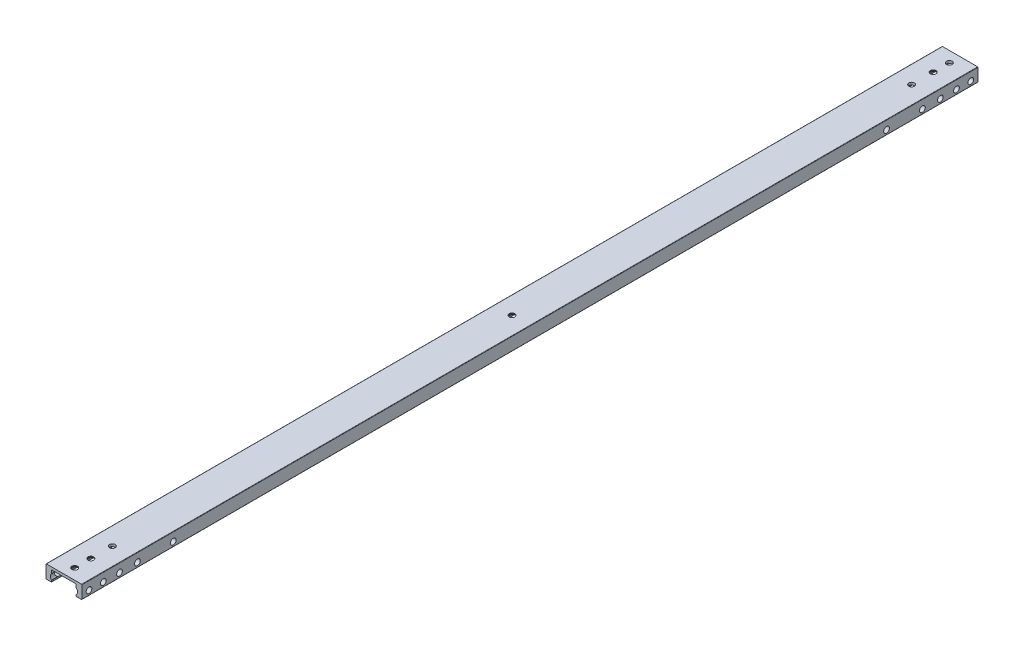
SolidWorks part; units mm, degrees
ref_plane "Front Plane" through (0, 0, 0) normal (0, 0, 1) x (1, 0, 0)
ref_plane "Top Plane" through (0, 0, 0) normal (0, 1, 0) x (1, 0, 0)
ref_plane "Right Plane" through (0, 0, 0) normal (1, 0, 0) x (0, 0, -1)
sketch "Sketch1" plane through (0, 0, 0) normal (0, 0, 1) x (1, 0, 0)
  line L0 (0, 3.7) -> (0, -3.7) construction
  line L1 (-10, -3.7) -> (10, -3.7)
  line L2 (-10, -3.7) -> (-10, 3.7)
  line L3 (-10, 3.7) -> (10, 3.7)
  line L4 (10, -3.7) -> (10, 3.7)
  line L5 (-10, -3.7) -> (10, 3.7) construction
  line L6 (-10, 3.7) -> (10, -3.7) construction
  line L7 (-6.85, -3.7) -> (6.85, -3.7)
  line L8 (-6.85, -3.7) -> (-6.85, 2.3)
  line L9 (-6.85, 2.3) -> (6.85, 2.3)
  line L10 (6.85, -3.7) -> (6.85, 2.3)
  line L11 (0, 2.3) -> (0, -3.7) construction
  point P0 (0, 0)
  dimension "D1" = 20
  dimension "D2" = 7.4
  dimension "D3" = 0
  dimension "D4" = 3.15
  dimension "D5" = 1.4
extrude "Boss-Extrude1" add sketch "Sketch1" along normal blind 500 contours L10 L1 L4 L3 L2 L8 L9
sketch "Sketch4" plane through (0, 2.3, 0) normal (0, -1, 0) x (1, 0, 0)
  line L0 (-10, 250) -> (10, 250) construction
  line L1 (-10, 500) -> (-10, 0) construction
  line L2 (10, 500) -> (10, 0) construction
  line L4 (-6.85, 500) -> (6.85, 500) construction
  circle A0 centre (0, 250) radius 1.6
  circle A1 centre (0, 15) radius 1.6
  circle A2 centre (0, 485) radius 1.6
  circle A5 centre (0, 494) radius 1.6
  circle A6 centre (0, 473) radius 1.6
  circle A7 centre (0, 27) radius 1.6
  circle A8 centre (0, 6) radius 1.6
  dimension "D1" = 3.2
  dimension "D2" = 3.2
  dimension "D4" = 3.2
  dimension "D6" = 9
  dimension "D7" = 3.2
  dimension "D3" = 235
  dimension "D5" = 15
  dimension "D8" = 12
extrude "Cut-Extrude1" cut sketch "Sketch4" against normal through all
sketch "Sketch5" plane through (0, 0, 500) normal (0, 0, 1) x (1, 0, 0)
  line L0 (0, 3.7) -> (0, -3.7178) construction
  line L1 (-10, 3.7) -> (10, 3.7) construction
  line L2 (-10, -3.7) -> (-6.85, -3.7) construction
  circle A0 centre (-5.7299, -1.15) radius 1.9
  circle A1 centre (5.7299, -1.15) radius 1.9
  dimension "D1" = 3.8
  dimension "D2" = 2.55
extrude "Cut-Extrude2" cut sketch "Sketch5" against normal through all
fillet "Fillet1" radius 0.2 12 edges at (-10, 3.7, 250) (-10, -3.7, 250) (-6.85, -3.7, 250) (-6.85, 0.3848, 250) (-6.85, -2.6848, 250) (-6.85, 2.3, 250) (10, 3.7, 250) (6.85, 2.3, 250) (6.85, -2.6848, 250) (6.85, 0.3848, 250) (6.85, -3.7, 250) (10, -3.7, 250)
sketch "Sketch6" plane through (-6.85, 0, 0) normal (1, 0, 0) x (0, 0, -1)
  line L0 (0, -2.6277) -> (0, 0.3277) construction
  line L1 (0, -2.6277) -> (0, 0.3277)
  line L2 (-250, 3.7) -> (-250, -3.5) construction
  line L3 (-500, 3.7) -> (0, 3.7) construction
  line L4 (-500, -3.5) -> (0, -3.5) construction
  circle A0 centre (-4, -1.15) radius 1.6
  circle A1 centre (-496, -1.15) radius 1.6
  circle A7 centre (-488, -1.15) radius 1.6
  circle A10 centre (-12, -1.15) radius 1.6
  circle A11 centre (-4, -1.15) radius 1.6
  circle A14 centre (-472, -1.15) radius 1.6 [skipped]
  circle A15 centre (-469, -1.15) radius 1.6
  circle A17 centre (-449, -1.15) radius 1.6
  circle A19 centre (-480, -1.15) radius 1.6 [skipped]
  circle A20 centre (-479, -1.15) radius 1.6
  circle A21 centre (-51, -1.15) radius 1.6
  circle A22 centre (-31, -1.15) radius 1.6
  circle A23 centre (-21, -1.15) radius 1.6
  dimension "D1" = 3.2
  dimension "D3" = 4
  dimension "D5" = 3.2
  dimension "D4" = 3.2
  dimension "D7" = 3.2
  dimension "D9" = 8
  dimension "D2" = 4
  dimension "D6" = 10
  dimension "D8" = 20
  dimension "D10" = 9
extrude "Cut-Extrude3" cut sketch "Sketch6" against normal through all and the other way through all contours A0 | A1
chamfer "Chamfer3" distance 1 angle 44 4 edges at (1.6, 2.3, 15) (1.6, 2.3, 250) (-1.6, 2.3, 485) (1.6, 2.3, 494)
